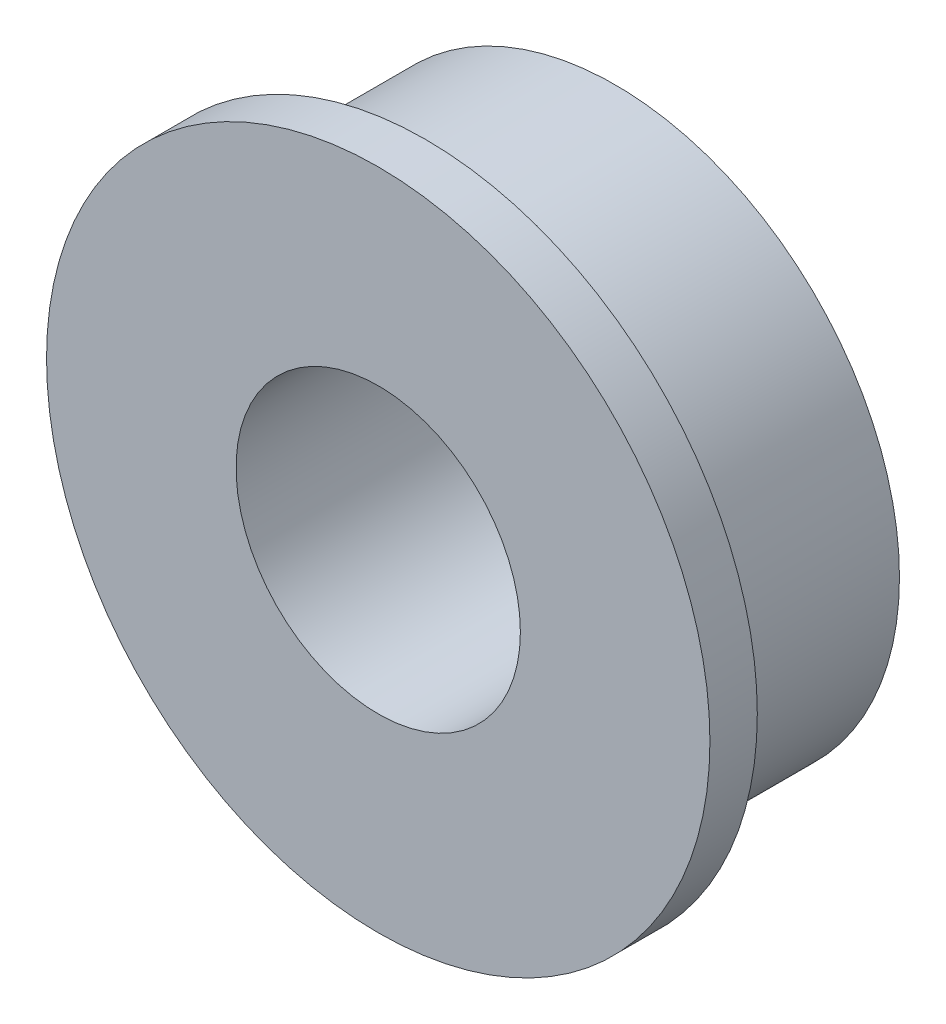
SolidWorks part; units mm, degrees
ref_plane "前视基准面" through (0, 0, 0) normal (0, 0, 1) x (1, 0, 0)
ref_plane "上视基准面" through (0, 0, 0) normal (0, 1, 0) x (1, 0, 0)
ref_plane "右视基准面" through (0, 0, 0) normal (1, 0, 0) x (0, 0, -1)
sketch "草图1" plane through (0, 0, 0) normal (0, 0, 1) x (1, 0, 0)
  circle A0 centre (0, 0) radius 1.5
  circle A1 centre (0, 0) radius 3
extrude "凸台-拉伸1" add sketch "草图1" along normal blind 2
sketch "草图2" plane through (0, 0, 2) normal (0, 0, 1) x (1, 0, 0)
  circle A0 centre (0, 0) radius 3.5
  circle A1 centre (0, 0) radius 1.5
extrude "凸台-拉伸3" add sketch "草图2" along normal blind 0.5
